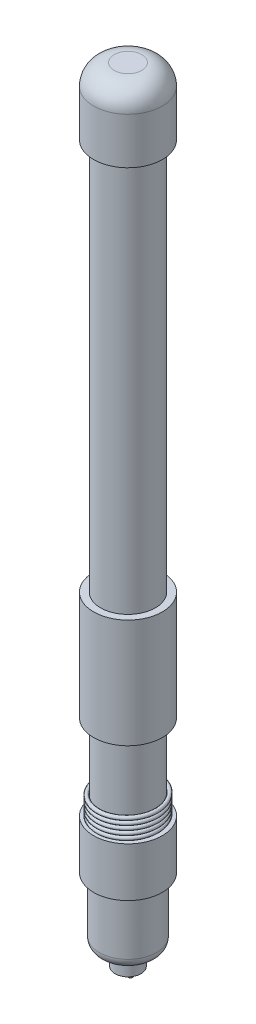
SolidWorks part; units mm, degrees
ref_plane "Front Plane" through (0, 0, 0) normal (0, 0, 1) x (1, 0, 0)
ref_plane "Top Plane" through (0, 0, 0) normal (0, 1, 0) x (1, 0, 0)
ref_plane "Right Plane" through (0, 0, 0) normal (1, 0, 0) x (0, 0, -1)
sketch "Sketch1" plane through (0, 0, 0) normal (0, 0, 1) x (1, 0, 0)
  line L0 (0, 0) -> (0, -192.9646) construction
  line L1 (0, 0) -> (-16.9545, 0)
  line L2 (-16.9545, 0) -> (-16.9545, -33.02)
  line L3 (-16.9545, -33.02) -> (-13.5255, -33.02)
  line L4 (-13.5255, -33.02) -> (-13.5255, -226.314)
  line L5 (-13.5255, -226.314) -> (-16.9545, -226.314)
  line L6 (-16.9545, -226.314) -> (-16.9545, -280.035)
  line L7 (-16.9545, -280.035) -> (-13.5255, -280.035)
  line L8 (-13.5255, -280.035) -> (-13.5255, -321.945)
  line L9 (-13.5255, -321.945) -> (-16.9545, -321.945)
  line L10 (-16.9545, -321.945) -> (-16.9545, -346.202)
  line L11 (-16.9545, -346.202) -> (-14.097, -346.202)
  line L12 (-14.097, -346.202) -> (-14.097, -378.4092)
  line L13 (-14.097, -378.4092) -> (-6.4008, -378.4092)
  line L14 (-6.4008, -378.4092) -> (-6.4008, -386.2451)
  line L15 (-6.4008, -386.2451) -> (0, -386.2451)
  line L16 (0, -386.2451) -> (0, 0)
  dimension "D1" = 33.909
  dimension "D2" = 27.051
  dimension "D3" = 28.194
  dimension "D4" = 12.8016
  dimension "D5" = 33.02
  dimension "D6" = 193.294
  dimension "D7" = 24.257
  dimension "D8" = 7.8359
  dimension "D9" = 32.2072
  dimension "D10" = 41.91
  dimension "D11" = 53.721
revolve "Revolve1" add sketch "Sketch1" angle 360 about L0
fillet "Fillet1" radius 10.16 1 edges at (0, 0, 16.9545)
fillet "Fillet2" radius 5.08 1 edges at (0, -378.4092, 14.097)
sketch "Sketch2" plane through (0, -321.945, 0) normal (0, 1, 0) x (1, 0, 0)
  circle A1 centre (0, 0) radius 14.478
  dimension "D1" = 28.956
curve "Helix/Spiral1" pitch 2.1389 height 10.16 turns 4.75
sketch "Sketch3" plane through (0, 0, 0) normal (0, 0, 1) x (1, 0, 0)
  line L0 (16.9545, -321.945) -> (-16.9545, -321.945) construction
  line L1 (-13.5255, -280.035) -> (-13.5255, -321.945) construction
  circle A0 centre (-14.478, -321.945) radius 0.9525
  spline S0 degree 3 poles (-14.478, -321.945) (-14.478, -321.9024) (-13.781, -321.8163) (-10.7919, -321.6878) (-6.2808, -321.5592) (-0.8839, -321.4306) (4.6377, -321.302) (9.5052, -321.1734) (13.0321, -321.0447) (14.7211, -320.9161) (14.3339, -320.7875) (11.9252, -320.6589) (7.8346, -320.5303) (2.6391, -320.4017) (-2.9286, -320.2731) (-8.0833, -320.1445) (-12.098, -320.0159) (-14.4065, -319.8873) (-14.6831, -319.7587) (-12.889, -319.6301) (-9.2771, -319.5015) (-4.3568, -319.3728) (1.178, -319.2442) (6.5466, -319.1156) (10.9919, -318.987) (13.887, -318.8584) (14.8236, -318.7298) (13.6695, -318.6012) (10.5876, -318.4726) (6.0125, -318.344) (0.5895, -318.2154) (-4.9168, -318.0868) (-9.7295, -317.9582) (-13.1701, -317.8296) (-14.7533, -317.7009) (-14.2558, -317.5723) (-11.7477, -317.4437) (-7.5828, -317.3151) (-2.3485, -317.1865) (3.217, -317.0579) (8.3289, -316.9293) (12.266, -316.8007) (14.4733, -316.6721) (14.6393, -316.5435) (12.7407, -316.4149) (9.0453, -316.2863) (4.0741, -316.1577) (-1.4716, -316.0291) (-6.8098, -315.9004) (-11.1876, -315.7718) (-13.9875, -315.6432) (-14.8148, -315.5146) (-13.5527, -315.386) (-10.3792, -315.2574) (-5.7419, -315.1288) (-0.2948, -315.0002) (5.1939, -314.8716) (9.95, -314.743) (13.3029, -314.6144) (14.7796, -314.4858) (14.1719, -314.3572) (11.5655, -314.2285) (7.328, -314.0999) (2.057, -313.9713) (-3.5042, -313.8427) (-8.5711, -313.7141) (-12.4292, -313.5855) (-14.5344, -313.4569) (-14.5897, -313.3283) (-12.5875, -313.1997) (-8.8099, -313.0711) (-3.7899, -312.9425) (1.7646, -312.8139) (7.0703, -312.6853) (11.3788, -312.5566) (14.0825, -312.428) (14.8, -312.2994) (13.4308, -312.1708) (10.1653, -312.0422) (5.4739, -311.9137) (1.8124, -311.8276) (0, -311.785) knots 0 0 0 0 0.012658 0.025316 0.037975 0.050633 0.063291 0.075949 0.088608 0.101266 0.113924 0.126582 0.139241 0.151899 0.164557 0.177215 0.189873 0.202532 0.21519 0.227848 0.240506 0.253165 0.265823 0.278481 0.291139 0.303797 0.316456 0.329114 0.341772 0.35443 0.367089 0.379747 0.392405 0.405063 0.417722 0.43038 0.443038 0.455696 0.468354 0.481013 0.493671 0.506329 0.518987 0.531646 0.544304 0.556962 0.56962 0.582278 0.594937 0.607595 0.620253 0.632911 0.64557 0.658228 0.670886 0.683544 0.696203 0.708861 0.721519 0.734177 0.746835 0.759494 0.772152 0.78481 0.797468 0.810127 0.822785 0.835443 0.848101 0.860759 0.873418 0.886076 0.898734 0.911392 0.924051 0.936709 0.949367 0.962025 0.974684 0.987342 1 1 1 1 construction
sweep "Sweep2" add profiles "Sketch3" path "Helix/Spiral1"
sketch "Sketch5" plane through (0, 0, 0) normal (0, 0, 1) x (1, 0, 0)
  line L0 (0, -384.9286) -> (0, -396.2859) construction
  line L1 (-2.921, -386.2451) -> (-2.921, -387.5151)
  line L2 (-6.4008, -386.2451) -> (6.4008, -386.2451) construction
  line L3 (2.921, -386.2451) -> (2.921, -387.5151)
  arc A0 (-2.921, -387.5151) -> (2.921, -387.5151) centre (0, -387.5151) ccw
  dimension "D3" = 2.921
  dimension "D1" = 5.842
  dimension "D2" = 1.27
sketch "Sketch6" plane through (0, -386.2451, 0) normal (0, -1, 0) x (1, 0, 0)
  circle A0 centre (-2.921, 0) radius 0.381
  dimension "D1" = 0.762
sweep "Sweep3" add profiles "Sketch6" path "Sketch5"
